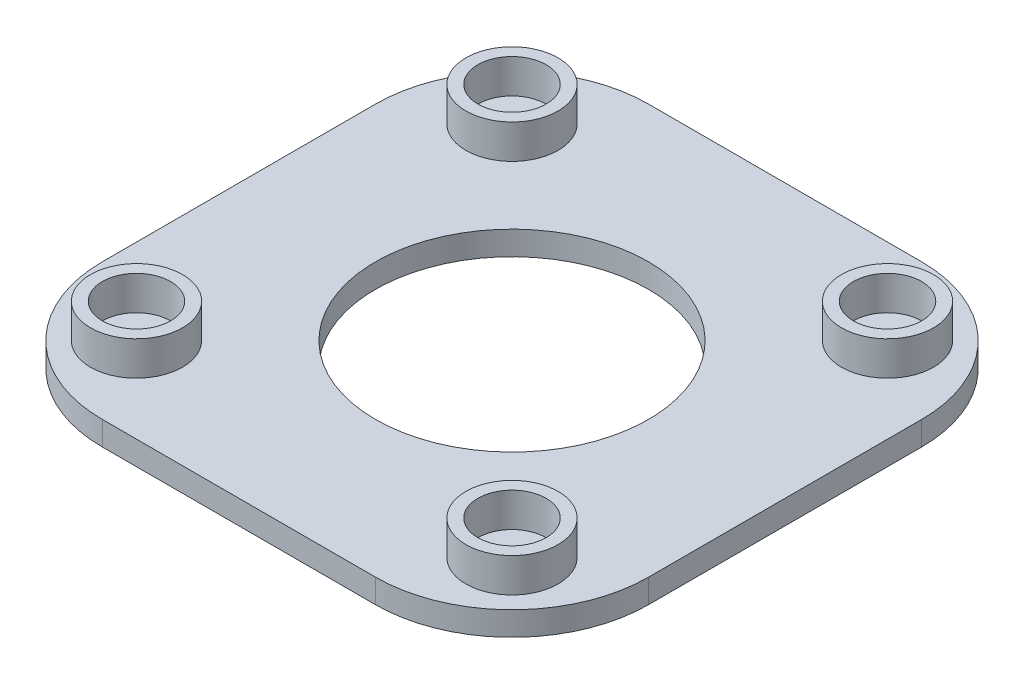
SolidWorks part; units mm, degrees
ref_plane "Front Plane" through (0, 0, 0) normal (0, 0, 1) x (1, 0, 0)
ref_plane "Top Plane" through (0, 0, 0) normal (0, 1, 0) x (1, 0, 0)
ref_plane "Right Plane" through (0, 0, 0) normal (1, 0, 0) x (0, 0, -1)
sketch "Çizim1" plane through (0, 0, 0) normal (0, 1, 0) x (1, 0, 0)
  line L0 (800, 400) -> (800, -400)
  line L1 (-400, -800) -> (400, -800)
  line L2 (-800, 400) -> (-800, -400)
  line L3 (400, 800) -> (-400, 800)
  arc A4 (800, 400) -> (400, 800) centre (400, 400) ccw
  arc A5 (800, -400) -> (400, -800) centre (400, -400) cw
  arc A6 (-800, -400) -> (-400, -800) centre (-400, -400) ccw
  arc A7 (-800, 400) -> (-400, 800) centre (-400, 400) cw
  circle A8 centre (0, 0) radius 400
  point P13 (0, 800)
  point P18 (800, 800)
  point P21 (800, -800)
  point P26 (-800, 800)
  dimension "D3" = 1600
  dimension "D7" = 400
  dimension "D8" = 800
  dimension "D4" = 800
  dimension "D5" = 800
  dimension "D6" = 800
extrude "Yükseklik-Ekstrüzyon1" add sketch "Çizim1" along normal blind 70
sketch "Çizim2" plane through (0, 70, 0) normal (0, 1, 0) x (1, 0, 0)
  circle A0 centre (-550, 550) radius 100
  circle A1 centre (550, 550) radius 100
  circle A2 centre (-550, -550) radius 100
  circle A3 centre (550, -550) radius 100
  circle A4 centre (-550, 550) radius 135
  circle A5 centre (550, 550) radius 135
  circle A6 centre (-550, -550) radius 135
  circle A7 centre (550, -550) radius 135
  dimension "D1" = 550
  dimension "D5" = 550
  dimension "D7" = 200
  dimension "D2" = 550
  dimension "D3" = 550
  dimension "D4" = 550
  dimension "D6" = 550
extrude "Yükseklik-Ekstrüzyon2" add sketch "Çizim2" along normal blind 100
